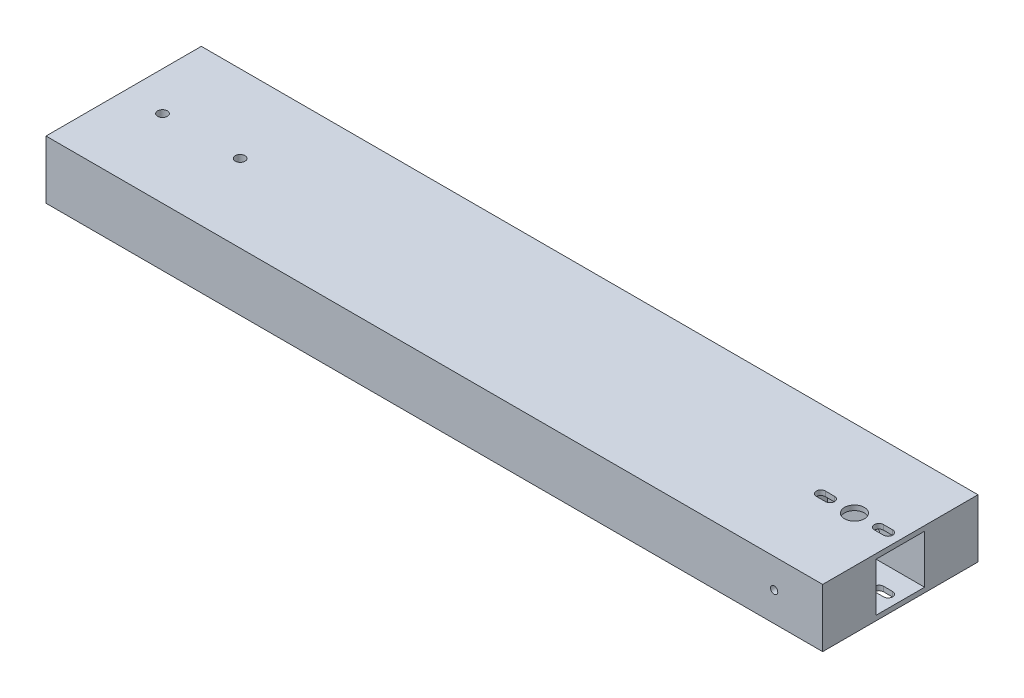
SolidWorks part; units mm, degrees
ref_plane "Front Plane" through (0, 0, 0) normal (0, 0, 1) x (1, 0, 0)
ref_plane "Top Plane" through (0, 0, 0) normal (0, 1, 0) x (1, 0, 0)
ref_plane "Right Plane" through (0, 0, 0) normal (1, 0, 0) x (0, 0, -1)
sketch "Sketch1" plane through (0, 0, 0) normal (0, 1, 0) x (1, 0, 0)
  line L1 (-127, -25.4) -> (127, -25.4)
  line L2 (-127, -25.4) -> (-127, 25.4)
  line L3 (-127, 25.4) -> (127, 25.4)
  line L4 (127, -25.4) -> (127, 25.4)
  line L5 (-127, -25.4) -> (127, 25.4) construction
  line L6 (-127, 25.4) -> (127, -25.4) construction
  point P0 (0, 0)
  dimension "D1" = 50.8
  dimension "D2" = 254
extrude "Boss-Extrude1" add sketch "Sketch1" along normal blind 19.05
sketch "Sketch2" plane through (0, 19.05, 0) normal (0, 1, 0) x (1, 0, 0)
  line L0 (-127, 25.4) -> (-127, -25.4) construction
  line L1 (122.9995, 0) -> (119.9998, 0) construction
  line L2 (122.9995, -1.5011) -> (119.9998, -1.5011)
  line L3 (122.9995, 1.5011) -> (119.9998, 1.5011)
  line L4 (127, -25.4) -> (127, 25.4) construction
  line L5 (104.0003, 0) -> (101.0006, 0) construction
  line L6 (104.0003, -1.5011) -> (101.0006, -1.5011)
  line L7 (104.0003, 1.5011) -> (101.0006, 1.5011)
  line L8 (-127, 25.4) -> (-127, -25.4) construction
  circle A0 centre (-114.3, 0) radius 1.5875
  circle A1 centre (-88.9, 0) radius 1.5875
  arc A2 (122.9995, -1.5011) -> (122.9995, 1.5011) centre (122.9995, 0) ccw
  arc A3 (119.9998, 1.5011) -> (119.9998, -1.5011) centre (119.9998, 0) ccw
  arc A4 (104.0003, -1.5011) -> (104.0003, 1.5011) centre (104.0003, 0) ccw
  arc A5 (101.0006, 1.5011) -> (101.0006, -1.5011) centre (101.0006, 0) ccw
  circle A6 centre (111.9988, 0) radius 3.2499
  point P4 (-127, 0)
  point P9 (121.4996, 0)
  point P15 (127, 0)
  point P20 (102.5004, 0)
  point P27 (127, 0)
  dimension "D3" = 3.175
  dimension "D4" = 3.175
  dimension "D6" = 1.5011
  dimension "D9" = 1.5011
  dimension "D11" = 6.4999
  dimension "D1" = 25.4
  dimension "D2" = 12.7
  dimension "D5" = 2.9997
  dimension "D7" = 4.0005
  dimension "D8" = 15.9995
  dimension "D10" = 2.9997
  dimension "D12" = 15.0012
  dimension "D13" = 38.1
extrude "Cut-Extrude1" cut sketch "Sketch2" against normal through all
sketch "Sketch3" plane through (0, 0, 25.4) normal (0, 0, 1) x (1, 0, 0)
  line L0 (127, 19.05) -> (127, 0) construction
  line L2 (27.94, 0) -> (-27.94, 0) construction
  circle A0 centre (111.125, 9.525) radius 1.1913
  dimension "D2" = 2.3825
  dimension "D1" = 15.875
  dimension "D3" = 9.525
extrude "Cut-Extrude2" cut sketch "Sketch3" against normal through all
sketch "Sketch4" plane through (127, 0, 0) normal (1, 0, 0) x (0, 0, -1)
  line L0 (27.94, 0) -> (-27.94, 0) construction
  line L1 (-7.9375, 17.4625) -> (7.9375, 17.4625)
  line L2 (-7.9375, 17.4625) -> (-7.9375, 1.5875)
  line L3 (-7.9375, 1.5875) -> (7.9375, 1.5875)
  line L4 (7.9375, 17.4625) -> (7.9375, 1.5875)
  line L5 (-7.9375, 17.4625) -> (7.9375, 1.5875) construction
  line L6 (-7.9375, 1.5875) -> (7.9375, 17.4625) construction
  point P0 (0, 9.525)
  dimension "D1" = 9.525
  dimension "D2" = 15.875
  dimension "D3" = 15.875
extrude "Cut-Extrude3" cut sketch "Sketch4" against normal blind 31.7551
